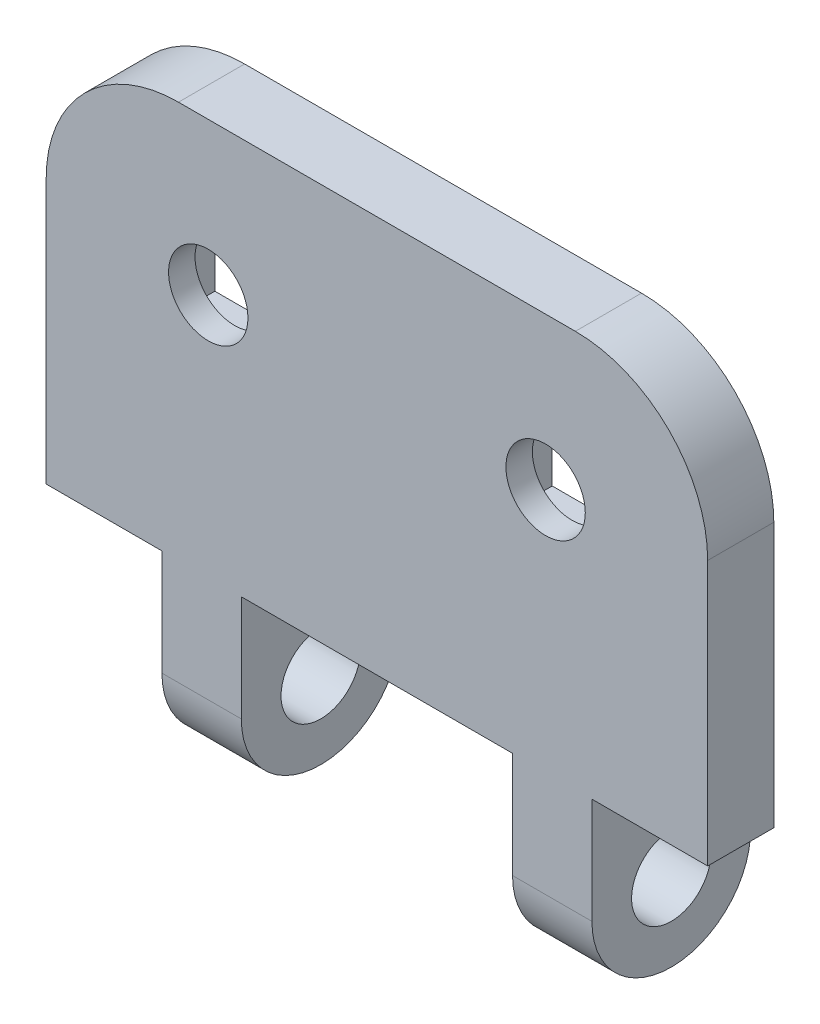
SolidWorks part; units mm, degrees
ref_plane "Alzado" through (0, 0, 0) normal (0, 0, 1) x (1, 0, 0)
ref_plane "Planta" through (0, 0, 0) normal (0, 1, 0) x (1, 0, 0)
ref_plane "Vista lateral" through (0, 0, 0) normal (1, 0, 0) x (0, 0, -1)
sketch "Croquis1" plane through (0, 0, 0) normal (0, 0, 1) x (1, 0, 0)
  line L1 (15, 15) -> (-15, 15)
  line L2 (25, 5) -> (25, -15)
  line L3 (25, -15) -> (-25, -15)
  line L4 (-25, 5) -> (-25, -15)
  line L5 (25, 15) -> (-25, -15) construction
  line L6 (25, -15) -> (-25, 15) construction
  arc A0 (15, 15) -> (25, 5) centre (15, 5) cw
  arc A1 (-15, 15) -> (-25, 5) centre (-15, 5) ccw
  point P0 (0, 0)
  dimension "D3" = 10
  dimension "D1" = 50
  dimension "D2" = 30
extrude "Saliente-Extruir1" add sketch "Croquis1" along normal blind 5
sketch "Croquis4" plane through (0, 0, 5) normal (0, 0, 1) x (1, 0, 0)
  line L0 (10.25, -15) -> (-10.25, -15)
  line L1 (-25, -15) -> (25, -15) construction
  line L2 (0, 0) -> (0, -15) construction
  line L3 (-10.25, -28) -> (10.25, -28) construction
  line L4 (-10.25, -15) -> (-16.25, -15)
  line L5 (-10.25, -15) -> (-10.25, -28)
  line L6 (-10.25, -28) -> (-16.25, -28)
  line L7 (-16.25, -15) -> (-16.25, -28)
  line L8 (10.25, -15) -> (16.25, -15)
  line L9 (10.25, -15) -> (10.25, -28)
  line L10 (10.25, -28) -> (16.25, -28)
  line L11 (16.25, -15) -> (16.25, -28)
  point P5 (0, -15)
  line M6 (-25, -15) -> (25, -15)
  dimension "D1" = 20.5
  dimension "D2" = 13
  dimension "D3" = 6
  dimension "D4" = 6
extrude "Saliente-Extruir2" add sketch "Croquis4" against normal up to surface (5 mm away) contours L7 L6 L5 M6 | L11 L9 L10 M6 up to face at (0, 2.357, 0)
sketch "Croquis6" plane through (16.25, 0, 0) normal (1, 0, 0) x (0, 0, -1)
  line L1 (0, -28) -> (-5, -28) construction
  line L2 (-5, -15) -> (-5, -28) construction
  circle A0 centre (1, -23) radius 6
  circle A1 centre (1, -23) radius 3
  dimension "D2" = 6
  dimension "D3" = 6
  dimension "D4" = 3
  dimension "D1" = 5
extrude "Saliente-Extruir3" add sketch "Croquis6" against normal up to surface (32.5 mm away) up to face at (-16.25, -21.5, 2.5)
sketch "Croquis7" plane through (-16.25, 0, 0) normal (-1, 0, 0) x (0, 0, 1)
  line L0 (7.6, -23) -> (5, -23)
  line L1 (5, -23) -> (-1, -29)
  line L2 (-1, -29) -> (-1, -31.6)
  circle A0 centre (-1, -23) radius 6
  circle A1 centre (-1, -23) radius 8.6
  circle A2 centre (-1, -23) radius 3
  line M1 (0, -20.1716) -> (0, -25.8284)
  arc M2 (0, -25.8284) -> (0, -20.1716) centre (-1, -23) cw
  line M5 (2.3166, -28) -> (5, -28)
  line M6 (5, -28) -> (5, -15)
extrude "Cortar-Extruir1" cut sketch "Croquis7" against normal through all both and the other way through all contours M1 M2 | A2 M1 | A0 M5 M6
sketch "Croquis8" plane through (0, 0, 0) normal (0, 0, -1) x (-1, 0, 0)
  line L0 (10.25, -15) -> (10.25, -30.5135) construction
  line L2 (-10.25, -15) -> (10.25, -15)
  line L3 (-10.25, -15) -> (-10.25, -30.5135)
  line L4 (-10.25, -30.5135) -> (10.25, -30.5135)
  line L5 (10.25, -15) -> (10.25, -30.5135)
extrude "Cortar-Extruir2" cut sketch "Croquis8" against normal through all both and the other way through all
sketch "Croquis9" plane through (0, 0, 5) normal (0, 0, 1) x (1, 0, 0)
  line L0 (0, 15) -> (0, 3.5) construction
  line L1 (15, 15) -> (-15, 15) construction
  line L2 (12.75, 3.5) -> (-12.75, 3.5) construction
  circle A0 centre (-12.75, 3.5) radius 3
  circle A1 centre (12.75, 3.5) radius 3
  point P8 (0, 3.5)
  dimension "D3" = 6
  dimension "D4" = 6
  dimension "D1" = 25.5
  dimension "D2" = 11.5
extrude "Cortar-Extruir3" cut sketch "Croquis9" against normal blind 6
sketch "Croquis10" plane through (0, 0, 0) normal (0, 0, -1) x (-1, 0, 0)
  line L1 (-17.25, -1) -> (-8.25, -1)
  line L2 (-17.25, -1) -> (-17.25, 8)
  line L3 (-17.25, 8) -> (-8.25, 8)
  line L4 (-8.25, -1) -> (-8.25, 8)
  line L5 (-17.25, -1) -> (-8.25, 8) construction
  line L6 (-17.25, 8) -> (-8.25, -1) construction
  line L7 (8.25, -1) -> (17.25, -1)
  line L8 (8.25, -1) -> (8.25, 8)
  line L9 (8.25, 8) -> (17.25, 8)
  line L10 (17.25, -1) -> (17.25, 8)
  line L11 (8.25, -1) -> (17.25, 8) construction
  line L12 (8.25, 8) -> (17.25, -1) construction
  point P0 (-12.75, 3.5)
  point P6 (12.75, 3.5)
  dimension "D1" = 9
  dimension "D2" = 9
  dimension "D3" = 9
  dimension "D4" = 9
extrude "Cortar-Extruir4" cut sketch "Croquis10" against normal blind 3 contours L2 L1 L4 L3 | L8 L7 L10 L9
